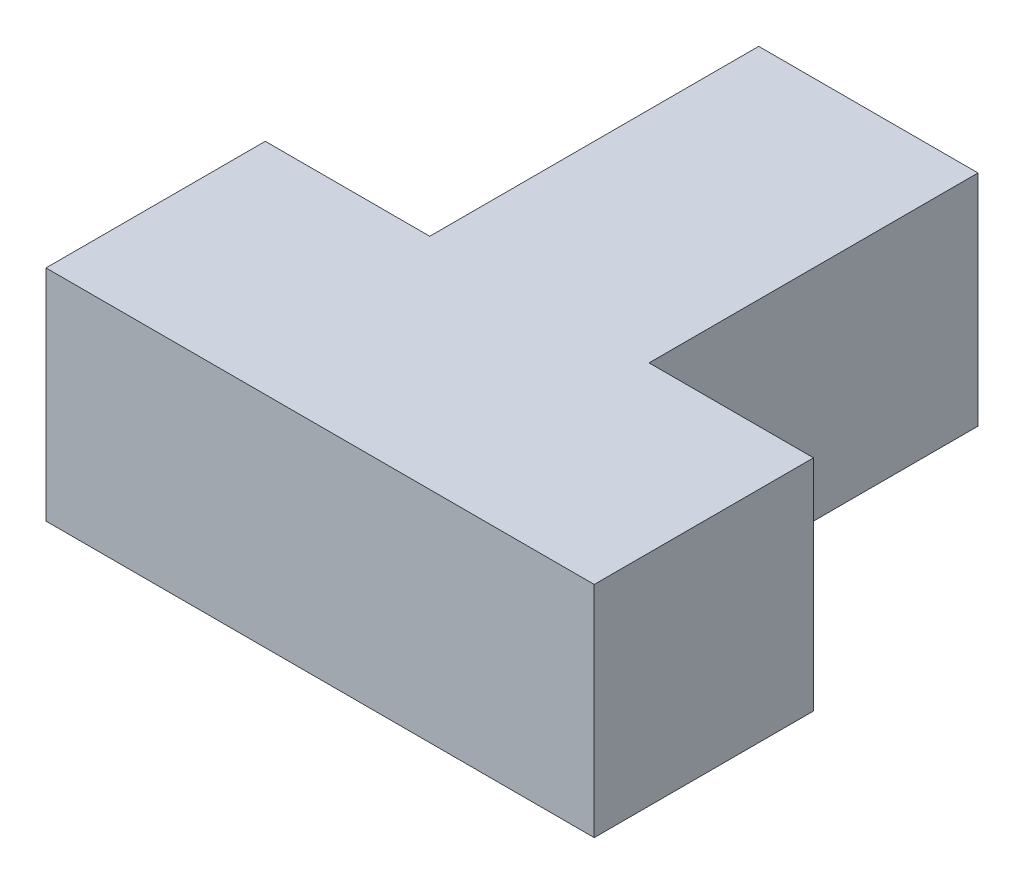
SolidWorks part; units mm, degrees
ref_plane "Front Plane" through (0, 0, 0) normal (0, 0, 1) x (1, 0, 0)
ref_plane "Top Plane" through (0, 0, 0) normal (0, 1, 0) x (1, 0, 0)
ref_plane "Right Plane" through (0, 0, 0) normal (1, 0, 0) x (0, 0, -1)
sketch "Sketch1" plane through (0, 0, 0) normal (0, 1, 0) x (1, 0, 0)
  line L0 (0, 0) -> (0, 25) construction
  line L1 (-25, -25) -> (25, -25)
  line L2 (-25, -25) -> (-25, -5)
  line L3 (-10, 25) -> (10, 25)
  line L4 (25, -25) -> (25, -5)
  line L5 (-25, -25) -> (10, 10) construction
  line L6 (-10, 10) -> (25, -25) construction
  line L9 (-25, -5) -> (-10, -5)
  line L10 (-10, 25) -> (-10, -5)
  line L11 (0, 25) -> (0, -25) construction
  line L12 (25, -5) -> (10, -5)
  line L13 (10, 25) -> (10, -5)
  point P0 (0, 0)
  dimension "D3" = 15
extrude "Boss-Extrude1" add sketch "Sketch1" along normal blind 20
